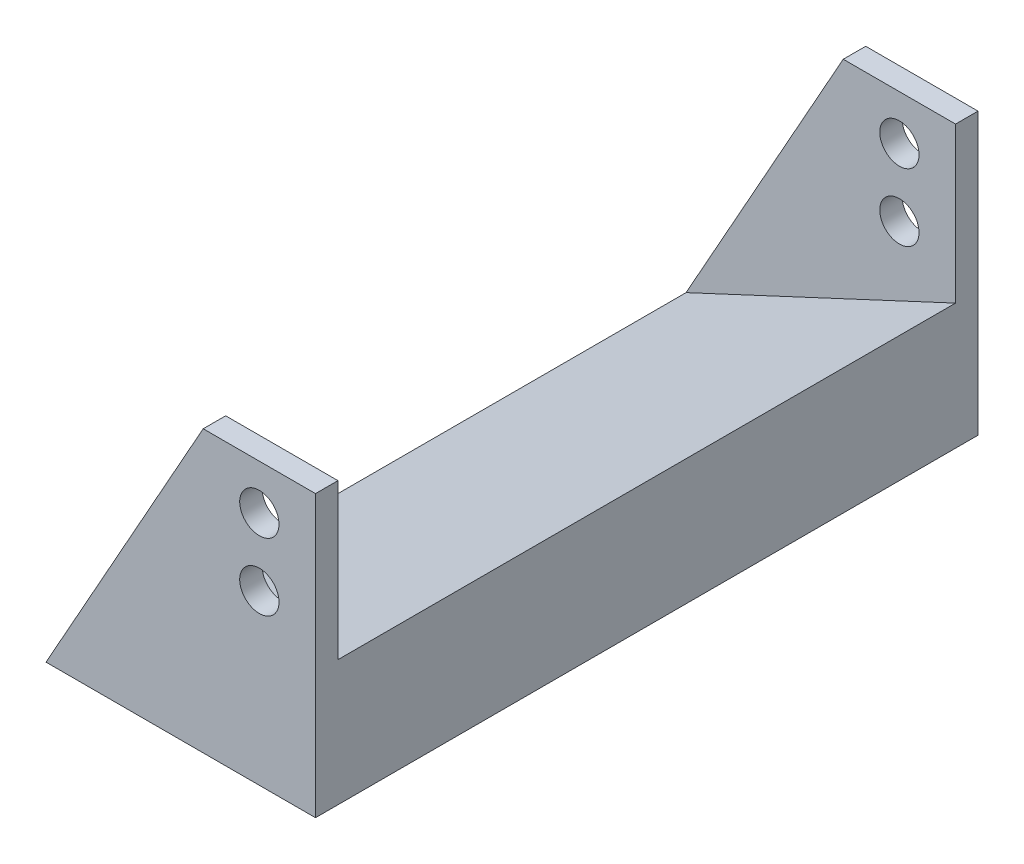
SolidWorks part; units mm, degrees
ref_plane "Front Plane" through (0, 0, 0) normal (0, 0, 1) x (1, 0, 0)
ref_plane "Top Plane" through (0, 0, 0) normal (0, 1, 0) x (1, 0, 0)
ref_plane "Right Plane" through (0, 0, 0) normal (1, 0, 0) x (0, 0, -1)
sketch "Sketch1" plane through (0, 0, 0) normal (0, 0, 1) x (1, 0, 0)
  line L0 (0, 0) -> (24, 0)
  line L1 (24, 0) -> (24, 11.1914)
  line L2 (24, 11.1914) -> (0, 0)
  dimension "D1" = 25
  dimension "D2" = 24
extrude "Boss-Extrude1" add sketch "Sketch1" along normal mid plane 55
sketch "Sketch2" plane through (0, 0, 27.5) normal (0, 0, 1) x (1, 0, 0)
  line L0 (24, 0) -> (24, 25)
  line L1 (24, 25) -> (14, 25)
  line L2 (14, 25) -> (0, 0)
  line L3 (0, 0) -> (24, 0)
  line L4 (19, 25) -> (19, 21) construction
  line L5 (19, 21) -> (19, 15) construction
  circle A0 centre (19, 21) radius 1.75
  circle A1 centre (19, 15) radius 1.75
  dimension "D5" = 3.5
  dimension "D1" = 25
  dimension "D2" = 10
  dimension "D3" = 4
  dimension "D4" = 6
extrude "Boss-Extrude2" add sketch "Sketch2" along normal blind 2
mirror "Mirror1" about plane through (0, 0, 0) normal (0, 0, 1) of "Boss-Extrude2"
